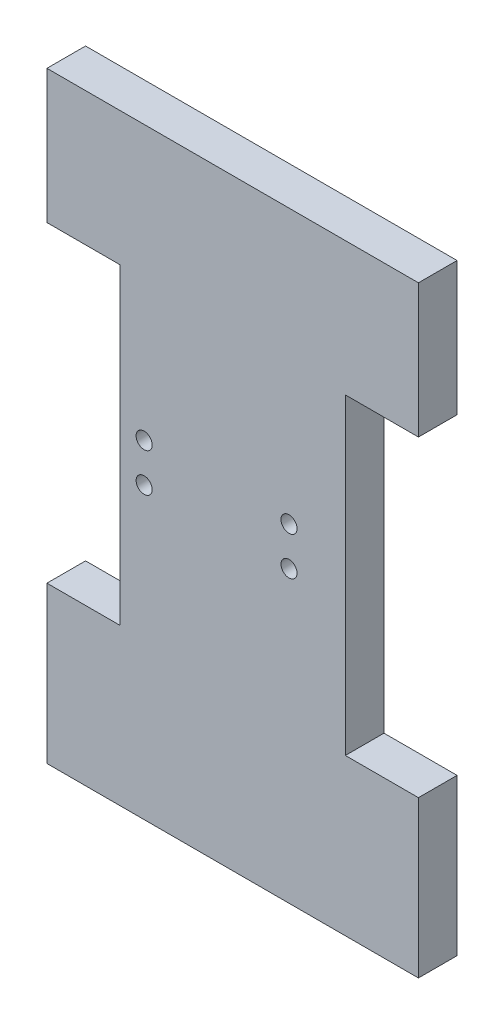
SolidWorks part; units mm, degrees
ref_plane "Front Plane" through (0, 0, 0) normal (0, 0, 1) x (1, 0, 0)
ref_plane "Top Plane" through (0, 0, 0) normal (0, 1, 0) x (1, 0, 0)
ref_plane "Right Plane" through (0, 0, 0) normal (1, 0, 0) x (0, 0, -1)
sketch "Sketch2" plane through (0, 0, 0) normal (0, 0, 1) x (1, 0, 0)
  line L0 (0, 0) -> (0, 40.4555) construction
  line L1 (0, 0) -> (53.8462, 0) construction
  line L2 (-57.7, 90) -> (57.7, 90)
  line L3 (57.7, 90) -> (57.7, 48.5)
  line L4 (57.7, 48.5) -> (35, 48.5)
  line L5 (35, 48.5) -> (35, -48.5)
  line L6 (35, -48.5) -> (57.7, -48.5)
  line L7 (57.7, -48.5) -> (57.7, -97.0125)
  line L8 (57.7, -97.0125) -> (-57.7, -97.0125)
  line L9 (-57.7, -48.5) -> (-57.7, -97.0125)
  line L10 (-35, -48.5) -> (-57.7, -48.5)
  line L11 (-35, 48.5) -> (-35, -48.5)
  line L12 (-57.7, 48.5) -> (-35, 48.5)
  line L13 (-57.7, 90) -> (-57.7, 48.5)
  point P13 (35, 0)
  point P19 (0, -97.0125)
  point P24 (0, 90)
  dimension "D1" = 70
  dimension "D2" = 115.4
  dimension "D3" = 90
  dimension "D4" = 97
  dimension "D5" = 97.0125
extrude "Boss-Extrude1" add sketch "Sketch2" along normal mid plane 12
hole_wizard "Tap Drill for M6x1.0 Tap1" positions "Sketch3" profile "Sketch4" hole size "M6x1.0" standard "ANSI Metric" end condition up to next
sketch "Sketch3" plane through (0, 0, -6) normal (0, 0, -1) x (-1, 0, 0)
  point P0 (-17.5, 5)
  point P3 (27.5, 5)
  point P6 (27.5, -7)
  point P9 (-17.5, -7)
sketch "Sketch4" plane through (17.5, 5, -6) normal (1, 0, 0) x (0, 1, 0)
  line L0 (0, 0) -> (0, 12)
  line L1 (0, 12) -> (2.5, 12)
  line L2 (2.5, 12) -> (2.5, 0)
  line L5 (2.5, 0) -> (0, 0)
  line L11 (0, -6.35) -> (0, 107.95) construction
  dimension "Thru Hole Dia." = 5
  dimension "Thru Hole Depth" = 12
hole_wizard "Tap Drill for M6x1.0 Tap2" positions "Sketch5" profile "Sketch6" hole size "M6x1.0" standard "ANSI Metric"
sketch "Sketch5" plane through (0, 0, -6) normal (0, 0, -1) x (-1, 0, 0)
  point P0 (-22.5, 5.5)
  point P3 (-22.5, -6.5)
  point P6 (22.5, 5.5)
  point P9 (22.5, -6.5)
sketch "Sketch6" plane through (22.5, 5.5, -6) normal (1, 0, 0) x (0, 1, 0)
  line L0 (0, 0) -> (0, 12)
  line L1 (0, 12) -> (2.5, 12)
  line L2 (2.5, 12) -> (2.5, 0)
  line L5 (2.5, 0) -> (0, 0)
  line L11 (0, -6.35) -> (0, 107.95) construction
  dimension "Thru Hole Dia." = 5
  dimension "Thru Hole Depth" = 12
